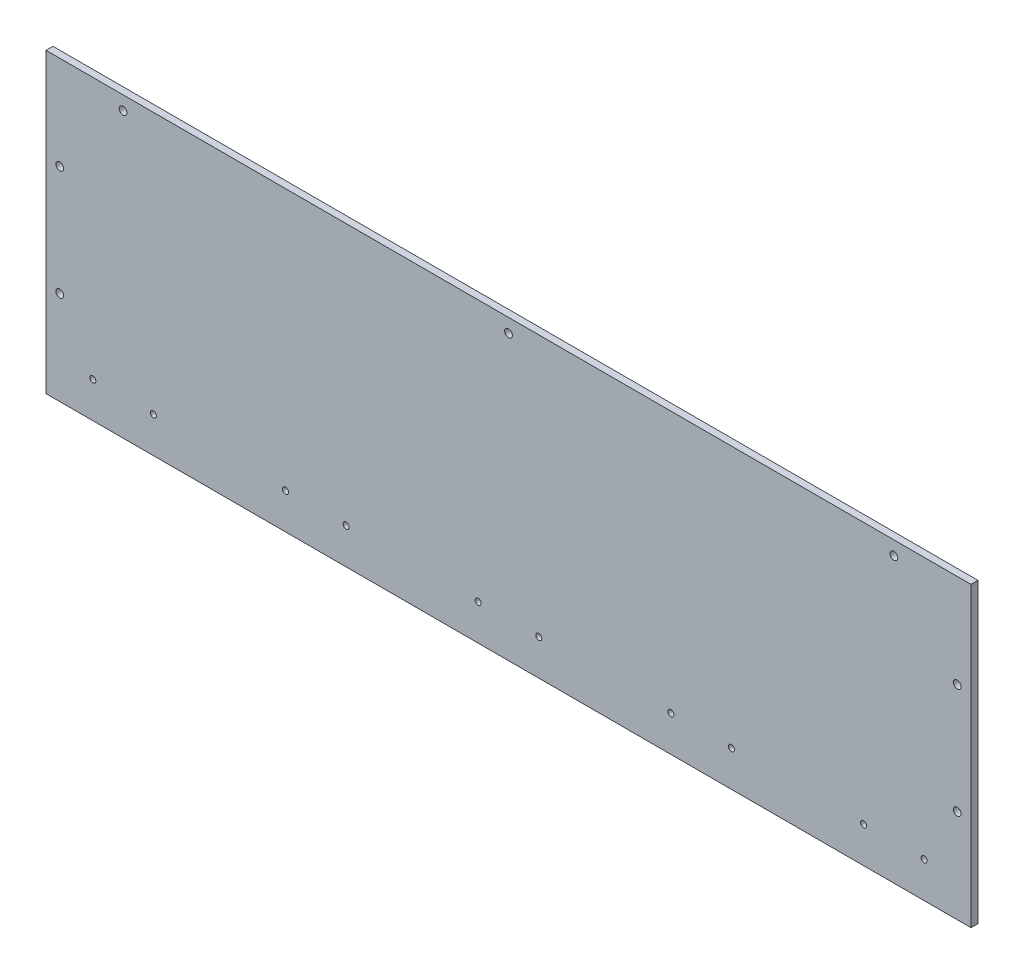
SolidWorks part; units mm, degrees
material "Acrylic (Medium-high impact)"
ref_plane "Front Plane" through (0, 0, 0) normal (0, 0, 1) x (1, 0, 0)
ref_plane "Top Plane" through (0, 0, 0) normal (0, 1, 0) x (1, 0, 0)
ref_plane "Right Plane" through (0, 0, 0) normal (1, 0, 0) x (0, 0, -1)
sketch "Sketch1" plane through (0, 0, 0) normal (0, 0, 1) x (1, 0, 0)
  line L1 (0, 0) -> (840, 0)
  line L2 (0, 0) -> (0, 270)
  line L3 (0, 270) -> (840, 270)
  line L4 (840, 0) -> (840, 270)
  dimension "D1" = 840
  dimension "D2" = 270
extrude "Boss-Extrude1" add sketch "Sketch1" along normal blind 6.35
ref_plane "Plane1" through (420, 0, 0) normal (-1, 0, 0) x (0, 0, 1)
sketch "Sketch2" plane through (0, 0, 6.35) normal (0, 0, 1) x (1, 0, 0)
  line L0 (420, 270) -> (420, 257.5) construction
  line L1 (840, 270) -> (0, 270) construction
  line L2 (70, 257.5) -> (770, 257.5) construction
  line L3 (0, 135) -> (12.5, 135) construction
  line L4 (0, 270) -> (0, 0) construction
  line L5 (12.5, 185) -> (12.5, 85) construction
  line L6 (420, 0) -> (420, 32.5) construction
  line L7 (392.5, 32.5) -> (567.5, 32.5) construction
  line L8 (0, 0) -> (840, 0) construction
  line L9 (392.5, 32.5) -> (447.5, 32.5) construction
  line L10 (392.5, 32.5) -> (217.5, 32.5) construction
  circle A0 centre (70, 257.5) radius 3.5
  circle A1 centre (420, 257.5) radius 3.5
  circle A2 centre (770, 257.5) radius 3.5
  circle A3 centre (12.5, 185) radius 3.5
  circle A4 centre (12.5, 85) radius 3.5
  circle A13 centre (392.5, 32.5) radius 2.75
  circle A14 centre (447.5, 32.5) radius 2.75
  circle A15 centre (567.5, 32.5) radius 2.75
  circle A16 centre (622.5, 32.5) radius 2.75
  circle A17 centre (742.5, 32.5) radius 2.75
  circle A18 centre (797.5, 32.5) radius 2.75
  circle A19 centre (217.5, 32.5) radius 2.75
  circle A20 centre (272.5, 32.5) radius 2.75
  circle A21 centre (42.5, 32.5) radius 2.75
  circle A22 centre (97.5, 32.5) radius 2.75
  point P6 (420, 257.5)
  point P16 (12.5, 135)
  point P25 (420, 32.5)
  dimension "D3" = 7
  dimension "D7" = 5.5
  dimension "D8" = 3
  dimension "D1" = 12.5
  dimension "D2" = 700
  dimension "D4" = 100
  dimension "D5" = 32.5
  dimension "D6" = 55
  dimension "D9" = 12.5
  dimension "D10" = 175
  dimension "D12" = 175
  dimension "D11" = 3
extrude "Cut-Extrude1" cut sketch "Sketch2" against normal through all and the other way through all
mirror "Mirror1" about plane through (420, 0, 0) normal (-1, 0, 0) of "Cut-Extrude1"
